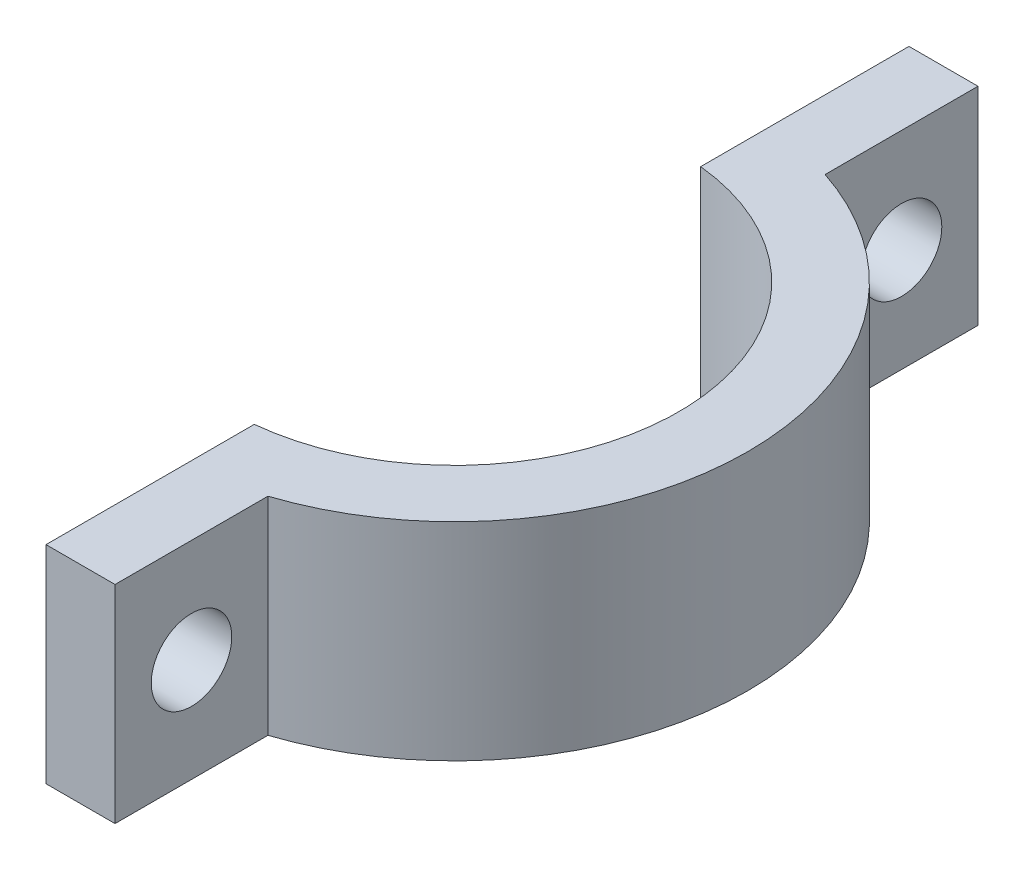
SolidWorks part; units mm, degrees
ref_plane "Front Plane" through (0, 0, 0) normal (0, 0, 1) x (1, 0, 0)
ref_plane "Top Plane" through (0, 0, 0) normal (0, 1, 0) x (1, 0, 0)
ref_plane "Right Plane" through (0, 0, 0) normal (1, 0, 0) x (0, 0, -1)
sketch "Sketch1" plane through (0, 0, 0) normal (0, 1, 0) x (1, 0, 0)
  line L9 (4, -18.75) -> (4, -12.1063)
  line L10 (1, -18.75) -> (1, -9.6986)
  line L11 (4, -18.75) -> (1, -18.75)
  line L12 (1, 18.75) -> (1, 9.6986)
  line L13 (4, 18.75) -> (1, 18.75)
  line L14 (4, 18.75) -> (4, 12.1063)
  arc A0 (1, -9.6986) -> (1, 9.6986) centre (0, 0) ccw
  arc A1 (4, -12.1063) -> (4, 12.1063) centre (0, 0) ccw
  circle A3 centre (0, 0) radius 9.75 construction
  circle A4 centre (0, 0) radius 12.75 construction
  point P1 (12.75, 0)
  point P5 (9.324, 2.8506)
  dimension "D1" = 19.5
  dimension "D2" = 3
extrude "Boss-Extrude1" add sketch "Sketch1" along normal blind 9
sketch "Sketch7" plane through (4, 0, 0) normal (1, 0, 0) x (0, 0, -1)
  circle A0 centre (-15.4282, 4.5) radius 1.75
  circle A1 centre (15.4282, 4.5) radius 1.75
  dimension "D1" = 3.5
  dimension "D2" = 3.5
extrude "Cut-Extrude1" cut sketch "Sketch7" against normal blind 10
